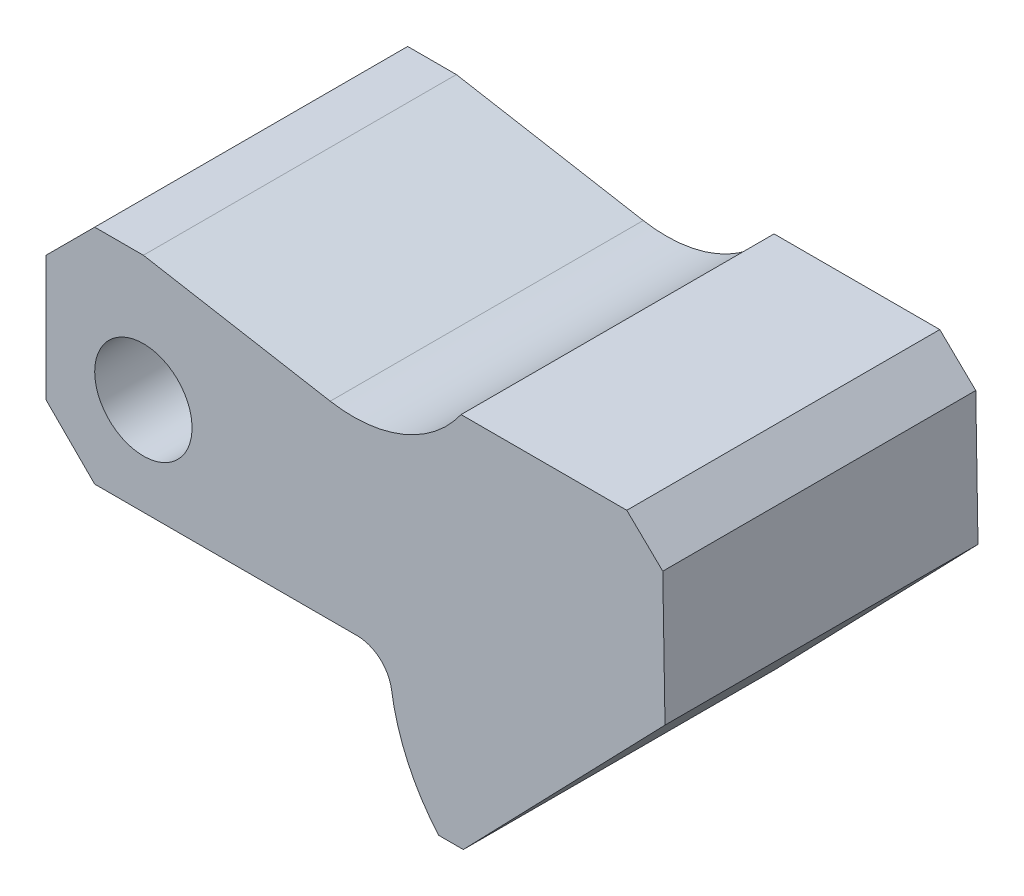
SolidWorks part; units mm, degrees
ref_plane "Front Plane" through (0, 0, 0) normal (0, 0, 1) x (1, 0, 0)
ref_plane "Top Plane" through (0, 0, 0) normal (0, 1, 0) x (1, 0, 0)
ref_plane "Right Plane" through (0, 0, 0) normal (1, 0, 0) x (0, 0, -1)
sketch "Sketch1" plane through (0, 0, 0) normal (0, 0, 1) x (1, 0, 0)
  line L0 (0, 0) -> (-7, 7)
  line L1 (-7, 7) -> (-7, 25)
  line L2 (-7, 25) -> (0, 32)
  line L3 (0, 32) -> (7, 32)
  line L4 (0, 0) -> (37.7363, 0)
  line L5 (49.4578, -19) -> (53, -19)
  line L6 (53, -19) -> (82, 11)
  line L7 (82, 11) -> (81.678, 30)
  line L8 (81.678, 30) -> (76.5056, 35)
  line L9 (76.5056, 35) -> (52.678, 35)
  line L10 (7, 32) -> (33.8681, 27.2624)
  arc A0 (33.8681, 27.2624) -> (52.678, 35) centre (37.1674, 45.9738) ccw
  circle A1 centre (7, 14) radius 7
  arc A2 (42.682, -4.2647) -> (49.4578, -19) centre (71.3667, 0) ccw
  arc A3 (42.682, -4.2647) -> (37.7363, 0) centre (37.7363, -5) ccw
  point P9 (71.3667, 0)
  dimension "D14" = 38
  dimension "D15" = 10
  dimension "D16" = 14
  dimension "D20" = 58
  dimension "D21" = 10
  dimension "D1" = 45
  dimension "D2" = 7
  dimension "D3" = 32
  dimension "D4" = 7
  dimension "D5" = 45
  dimension "D6" = 14
  dimension "D7" = 29
  dimension "D8" = 45
  dimension "D9" = 5
  dimension "D10" = 24
  dimension "D11" = 54
  dimension "D12" = 29
  dimension "D13" = 89
  dimension "D17" = 14
  dimension "D18" = 14
  dimension "D19" = 19
  dimension "D22" = 19
extrude "Boss-Extrude1" add sketch "Sketch1" along normal blind 45
